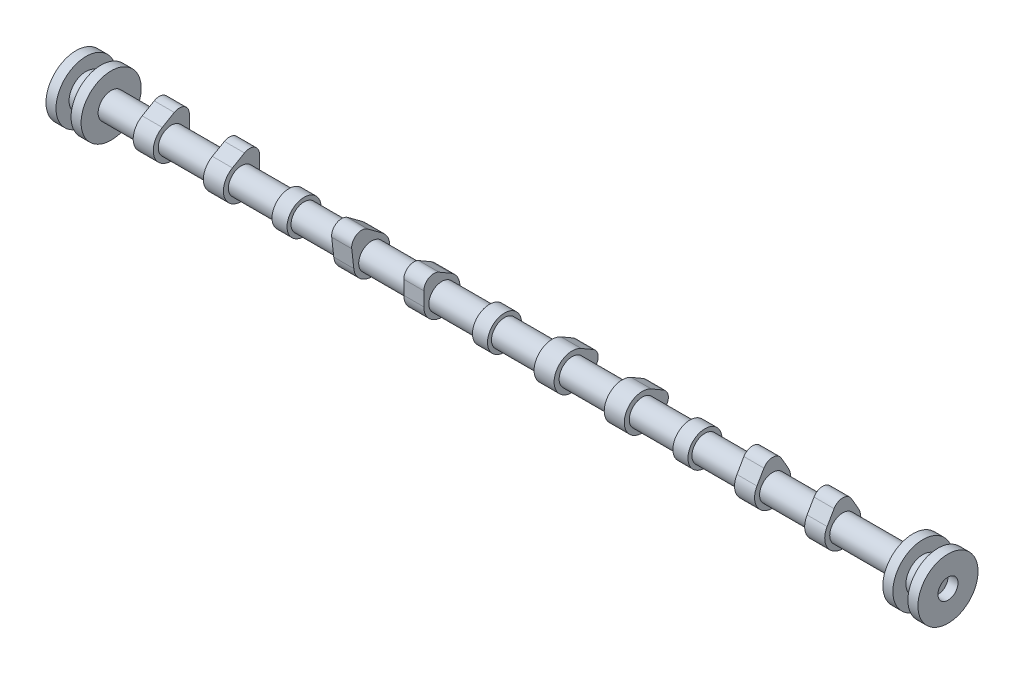
SolidWorks part; units mm, degrees
material "Alloy Steel"
ref_plane "Front Plane" through (0, 0, 0) normal (0, 0, 1) x (1, 0, 0)
ref_plane "Top Plane" through (0, 0, 0) normal (0, 1, 0) x (1, 0, 0)
ref_plane "Right Plane" through (0, 0, 0) normal (1, 0, 0) x (0, 0, -1)
sketch "Sketch2" plane through (0, 0, 0) normal (0, 1, 0) x (1, 0, 0)
  line L0 (-217.5, 0) -> (217.5, 0)
  line L1 (217.5, 0) -> (217.5, 15)
  line L2 (217.5, 15) -> (212.5, 15)
  line L3 (212.5, 15) -> (212.5, 8.5)
  line L4 (212.5, 8.5) -> (205, 8.5)
  line L5 (205, 8.5) -> (205, 15)
  line L6 (205, 15) -> (200, 15)
  line L7 (200, 15) -> (200, 6.5)
  line L8 (200, 6.5) -> (96.25, 6.5)
  line L9 (-200, 6.5) -> (-200, 15)
  line L10 (-200, 15) -> (-205, 15)
  line L11 (-205, 15) -> (-205, 8.5)
  line L12 (-205, 8.5) -> (-212.5, 8.5)
  line L13 (-212.5, 8.5) -> (-212.5, 15)
  line L14 (-212.5, 15) -> (-217.5, 15)
  line L15 (-217.5, 15) -> (-217.5, 6.5)
  line L17 (-217.5, 6.5) -> (-217.5, 0)
  line L18 (-111.25, 6.5) -> (-111.25, 8.5)
  line L19 (-111.25, 8.5) -> (-103.75, 8.5)
  line L20 (-103.75, 8.5) -> (-103.75, 6.5)
  line L21 (-11.25, 6.5) -> (-11.25, 8.5)
  line L22 (-11.25, 8.5) -> (-3.75, 8.5)
  line L23 (-3.75, 8.5) -> (-3.75, 6.5)
  line L24 (88.75, 6.5) -> (88.75, 8.5)
  line L25 (88.75, 8.5) -> (96.25, 8.5)
  line L26 (96.25, 8.5) -> (96.25, 6.5)
  line L27 (-111.25, 6.5) -> (-200, 6.5)
  line L28 (-11.25, 6.5) -> (-103.75, 6.5)
  line L29 (88.75, 6.5) -> (-3.75, 6.5)
  point P3 (0, 0)
  point P33 (-208.75, 8.5)
  point P34 (-107.5, 8.5)
  point P35 (-7.5, 8.5)
  point P36 (92.5, 8.5)
  dimension "D1" = 435
  dimension "D2" = 6.5
  dimension "D3" = 15
  dimension "D5" = 5
  dimension "D6" = 7.5
  dimension "D7" = 8.5
  dimension "D8" = 101.25
  dimension "D9" = 100
  dimension "D10" = 100
revolve "Revolve1" add sketch "Sketch2" angle 360 about L0
sketch "Sketch3" plane through (0, 0, 0) normal (0, 1, 0) x (1, 0, 0)
  line L2 (125, 17.5) -> (160, 17.5) construction
  line L3 (125, 17.5) -> (125, -17.5) construction
  line L4 (125, -17.5) -> (160, -17.5) construction
  line L5 (160, 17.5) -> (160, -17.5) construction
  line L6 (25, 17.5) -> (60, 17.5) construction
  line L7 (25, 17.5) -> (25, -17.5) construction
  line L8 (25, -17.5) -> (60, -17.5) construction
  line L9 (60, 17.5) -> (60, -17.5) construction
  line L10 (-75, 17.5) -> (-40, 17.5) construction
  line L11 (-75, 17.5) -> (-75, -17.5) construction
  line L12 (-75, -17.5) -> (-40, -17.5) construction
  line L13 (-40, 17.5) -> (-40, -17.5) construction
  line L14 (-175, 17.5) -> (-140, 17.5) construction
  line L15 (-175, 17.5) -> (-175, -17.5) construction
  line L16 (-175, -17.5) -> (-140, -17.5) construction
  line L17 (-140, 17.5) -> (-140, -17.5) construction
  circle A0 centre (142.5, 0) radius 45 construction
  circle A1 centre (-157.5, 0) radius 45 construction
  circle A2 centre (-57.5, 0) radius 45 construction
  circle A3 centre (42.5, 0) radius 45 construction
  circle A4 centre (160, 17.5) radius 10
  circle A5 centre (160, -17.5) radius 10
  circle A6 centre (125, -17.5) radius 10
  circle A7 centre (125, 17.5) radius 10
  circle A8 centre (60, 17.5) radius 10
  circle A9 centre (60, -17.5) radius 10
  circle A10 centre (25, -17.5) radius 10
  circle A11 centre (25, 17.5) radius 10
  circle A12 centre (-40, 17.5) radius 10
  circle A13 centre (-40, -17.5) radius 10
  circle A14 centre (-75, -17.5) radius 10
  circle A15 centre (-75, 17.5) radius 10
  circle A16 centre (-140, 17.5) radius 10
  circle A17 centre (-140, -17.5) radius 10
  circle A18 centre (-175, -17.5) radius 10
  circle A19 centre (-175, 17.5) radius 10
  circle A20 centre (-157.5, 0) radius 7.5
  circle A21 centre (-57.5, 0) radius 7.5
  circle A22 centre (42.5, 0) radius 7.5
  circle A23 centre (142.5, 0) radius 7.5
  point P27 (125, 0)
  point P28 (142.5, 17.5)
  point P29 (42.5, 17.5)
  point P30 (-57.5, 17.5)
  point P31 (-157.5, 17.5)
  dimension "D2" = 90
  dimension "D7" = 20
  dimension "D8" = 15
  dimension "D3" = 100
  dimension "D4" = 100
  dimension "D5" = 100
  dimension "D6" = 35
ref_plane "Plane1" through (-175, 0, 0) normal (1, 0, 0) x (0, 0, -1)
ref_plane "Plane2" through (-140, 0, 0) normal (1, 0, 0) x (0, 0, -1)
ref_plane "Plane3" through (-75, 0, 0) normal (1, 0, 0) x (0, 0, -1)
ref_plane "Plane4" through (-40, 0, 0) normal (1, 0, 0) x (0, 0, -1)
ref_plane "Plane5" through (25, 0, 0) normal (1, 0, 0) x (0, 0, -1)
ref_plane "Plane6" through (60, 0, 0) normal (1, 0, 0) x (0, 0, -1)
ref_plane "Plane7" through (125, 0, 0) normal (1, 0, 0) x (0, 0, -1)
ref_plane "Plane8" through (160, 0, 0) normal (1, 0, 0) x (0, 0, -1)
sketch "Sketch4" plane through (-175, 0, 0) normal (1, 0, 0) x (0, 0, -1)
  line L0 (4, 6.9282) -> (0, 0) construction
  line L1 (-4.5, 7.7942) -> (1.5, 11.2583)
  line L2 (9, 0) -> (9, 6.9282)
  line L3 (0, 0) -> (0, 33.9938) construction
  arc A0 (-4.5, 7.7942) -> (9, 0) centre (0, 0) ccw
  arc A1 (9, 6.9282) -> (1.5, 11.2583) centre (4, 6.9282) ccw
  dimension "D2" = 18
  dimension "D3" = 10
  dimension "D1" = 8
  dimension "D4" = 30
sketch "Sketch5" plane through (-140, 0, 0) normal (1, 0, 0) x (0, 0, -1)
  line L0 (4, 6.9282) -> (0, 0) construction
  line L1 (-4.5, 7.7942) -> (1.5, 11.2583)
  line L2 (9, 0) -> (9, 6.9282)
  line L3 (0, 0) -> (0, 33.9938) construction
  arc A0 (-4.5, 7.7942) -> (9, 0) centre (0, 0) ccw
  arc A1 (9, 6.9282) -> (1.5, 11.2583) centre (4, 6.9282) ccw
  dimension "D2" = 18
  dimension "D3" = 10
  dimension "D1" = 8
  dimension "D4" = 30
sketch "Sketch6" plane through (-75, 0, 0) normal (1, 0, 0) x (0, 0, -1)
  line L0 (-5, 8.6603) -> (0, 0) construction
  line L1 (-8.9435, -1.0066) -> (-9.9686, 8.101)
  line L2 (5.3435, 7.242) -> (-2.0314, 12.6836)
  line L3 (0, 0) -> (0, 33.9938) construction
  arc A0 (-8.9435, -1.0066) -> (5.3435, 7.242) centre (0, 0) ccw
  arc A1 (-2.0314, 12.6836) -> (-9.9686, 8.101) centre (-5, 8.6603) ccw
  dimension "D2" = 18
  dimension "D3" = 10
  dimension "D1" = 10
  dimension "D4" = 150
sketch "Sketch7" plane through (-40, 0, 0) normal (1, 0, 0) x (0, 0, -1)
  line L0 (-4, 6.9282) -> (0, 0) construction
  line L1 (-9, 0) -> (-9, 6.9282)
  line L2 (4.5, 7.7942) -> (-1.5, 11.2583)
  line L3 (0, 0) -> (0, 33.9938) construction
  arc A0 (-9, 0) -> (4.5, 7.7942) centre (0, 0) ccw
  arc A1 (-1.5, 11.2583) -> (-9, 6.9282) centre (-4, 6.9282) ccw
  dimension "D2" = 18
  dimension "D3" = 10
  dimension "D1" = 8
  dimension "D4" = 330
sketch "Sketch8" plane through (25, 0, 0) normal (1, 0, 0) x (0, 0, -1)
  line L0 (8, 0) -> (0, 0) construction
  line L1 (4.5, 7.7942) -> (10.5, 4.3301)
  line L2 (4.5, -7.7942) -> (10.5, -4.3301)
  line L3 (0, 0) -> (0, 33.9938) construction
  arc A0 (4.5, 7.7942) -> (4.5, -7.7942) centre (0, 0) ccw
  arc A1 (10.5, -4.3301) -> (10.5, 4.3301) centre (8, 0) ccw
  dimension "D2" = 18
  dimension "D3" = 10
  dimension "D1" = 8
  dimension "D4" = 90
sketch "Sketch9" plane through (60, 0, 0) normal (1, 0, 0) x (0, 0, -1)
  line L0 (8, 0) -> (0, 0) construction
  line L1 (4.5, 7.7942) -> (10.5, 4.3301)
  line L2 (4.5, -7.7942) -> (10.5, -4.3301)
  line L3 (0, 0) -> (0, 33.9938) construction
  arc A0 (4.5, 7.7942) -> (4.5, -7.7942) centre (0, 0) ccw
  arc A1 (10.5, -4.3301) -> (10.5, 4.3301) centre (8, 0) ccw
  dimension "D2" = 18
  dimension "D3" = 10
  dimension "D1" = 8
  dimension "D4" = 90
sketch "Sketch10" plane through (125, 0, 0) normal (1, 0, 0) x (0, 0, -1)
  line L0 (0, 8) -> (0, 0) construction
  line L1 (-7.7942, 4.5) -> (-4.3301, 10.5)
  line L2 (7.7942, 4.5) -> (4.3301, 10.5)
  line L3 (0, 0) -> (0, 33.9938) construction
  arc A0 (-7.7942, 4.5) -> (7.7942, 4.5) centre (0, 0) ccw
  arc A1 (4.3301, 10.5) -> (-4.3301, 10.5) centre (0, 8) ccw
  dimension "D2" = 18
  dimension "D3" = 10
  dimension "D1" = 8
  dimension "D4" = 0
sketch "Sketch11" plane through (160, 0, 0) normal (1, 0, 0) x (0, 0, -1)
  line L0 (0, 8) -> (0, 0) construction
  line L1 (-7.7942, 4.5) -> (-4.3301, 10.5)
  line L2 (7.7942, 4.5) -> (4.3301, 10.5)
  line L3 (0, 0) -> (0, 33.9938) construction
  arc A0 (-7.7942, 4.5) -> (7.7942, 4.5) centre (0, 0) ccw
  arc A1 (4.3301, 10.5) -> (-4.3301, 10.5) centre (0, 8) ccw
  dimension "D2" = 18
  dimension "D3" = 10
  dimension "D1" = 8
  dimension "D4" = 0
extrude "Boss-Extrude1" add sketch "Sketch4" along normal blind 5 and the other way blind 5
extrude "Boss-Extrude2" add sketch "Sketch5" along normal blind 5 and the other way blind 5
extrude "Boss-Extrude3" add sketch "Sketch6" along normal blind 5 and the other way blind 5
extrude "Boss-Extrude4" add sketch "Sketch7" along normal blind 5 and the other way blind 5
extrude "Boss-Extrude5" add sketch "Sketch8" along normal blind 5 and the other way blind 5
extrude "Boss-Extrude6" add sketch "Sketch9" along normal blind 5 and the other way blind 5
extrude "Boss-Extrude7" add sketch "Sketch10" along normal blind 5 and the other way blind 5
extrude "Boss-Extrude8" add sketch "Sketch11" along normal blind 5 and the other way blind 5
sketch "Sketch12" plane through (-217.5, 0, 0) normal (-1, 0, 0) x (0, 0, 1)
  circle A0 centre (0, 0) radius 5
  dimension "D1" = 10
extrude "Cut-Extrude1" cut sketch "Sketch12" against normal blind 5
mirror "Mirror1" about plane through (0, 0, 0) normal (1, 0, 0) of "Cut-Extrude1"
equation "\"d\"= 8"
equation "\"r1\"= 18"
equation "\"r2\"= 10"
equation "\"D1@Sketch4\"=\"d\""
equation "\"D2@Sketch4\"=\"r1\""
equation "\"D2@Sketch5\"=\"r1\""
equation "\"D1@Sketch5\"=\"d\""
equation "\"D3@Sketch5\"=\"r2\""
equation "\"D2@Sketch6\"=\"r1\""
equation "\"D3@Sketch6\"=\"r2\""
equation "\"D3@Sketch7\"=\"r2\""
equation "\"D2@Sketch7\"=\"r1\""
equation "\"D1@Sketch7\"=\"d\""
equation "\"D3@Sketch8\"=\"r2\""
equation "\"D1@Sketch8\"=\"d\""
equation "\"D2@Sketch8\"=\"r1\""
equation "\"D2@Sketch9\"=\"r1\""
equation "\"D3@Sketch9\"=\"r2\""
equation "\"D1@Sketch9\"=\"d\""
equation "\"D2@Sketch10\"=\"r1\""
equation "\"D3@Sketch10\"=\"r2\""
equation "\"D1@Sketch10\"=\"d\""
equation "\"D2@Sketch11\"=\"r1\""
equation "\"D3@Sketch11\"=\"r2\""
equation "\"D1@Sketch11\"=\"d\""
